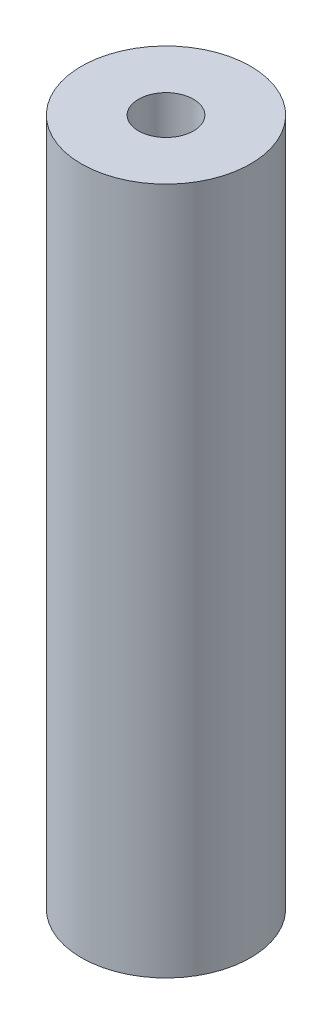
SolidWorks part; units mm, degrees
material "1060 合金"
ref_plane "正面" through (0, 0, 0) normal (0, 0, 1) x (1, 0, 0)
ref_plane "平面" through (0, 0, 0) normal (0, 1, 0) x (1, 0, 0)
ref_plane "右側面" through (0, 0, 0) normal (1, 0, 0) x (0, 0, -1)
sketch "ｽｹｯﾁ1" plane through (0, 0, 0) normal (0, 1, 0) x (1, 0, 0)
  circle A0 centre (0, 0) radius 4
  dimension "D1" = 8
extrude "ﾎﾞｽ - 押し出し1" add sketch "ｽｹｯﾁ1" along normal blind 32.5
sketch "ｽｹｯﾁ2" plane through (0, 32.5, 0) normal (0, 1, 0) x (1, 0, 0)
  circle A0 centre (0, 0) radius 1.3
  dimension "D1" = 2.6
extrude "ｶｯﾄ - 押し出し1" cut sketch "ｽｹｯﾁ2" against normal blind 10
sketch "ｽｹｯﾁ3" plane through (0, 0, 0) normal (0, -1, 0) x (1, 0, 0)
  circle A0 centre (0, 0) radius 1.3
  dimension "D1" = 2.6
extrude "ｶｯﾄ - 押し出し2" cut sketch "ｽｹｯﾁ3" against normal blind 12
